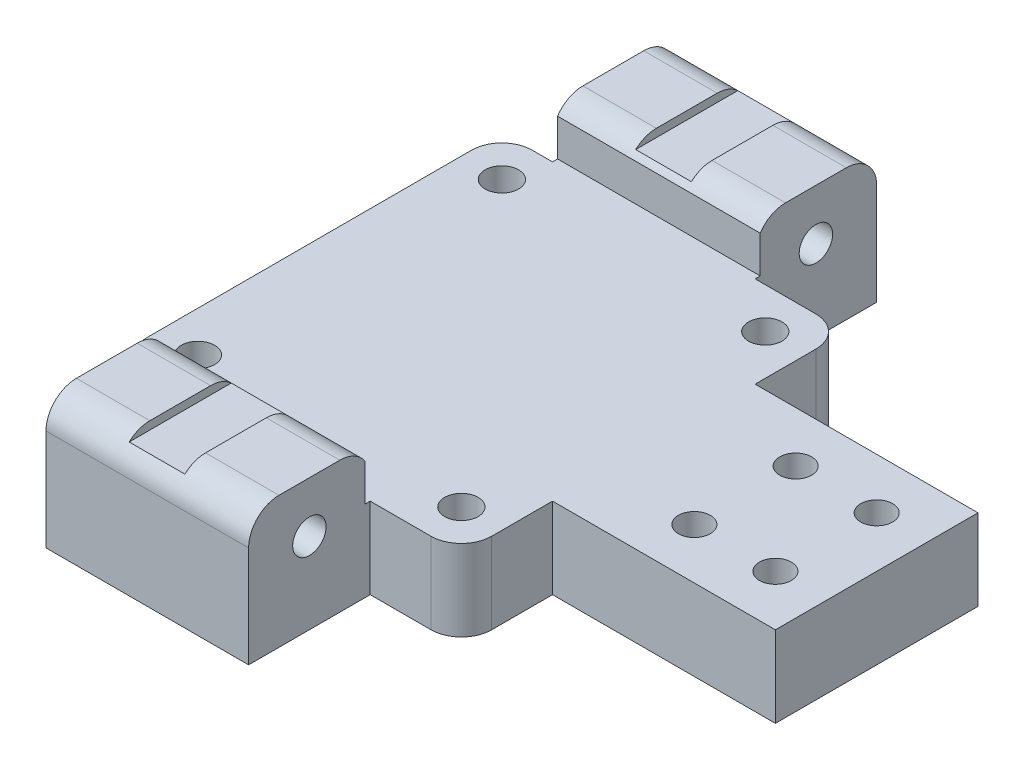
SolidWorks part; units mm, degrees
ref_plane "Front" through (0, 0, 0) normal (0, 0, 1) x (1, 0, 0)
ref_plane "Top" through (0, 0, 0) normal (0, 1, 0) x (1, 0, 0)
ref_plane "Right" through (0, 0, 0) normal (1, 0, 0) x (0, 0, -1)
sketch "Sketch1" plane through (0, 0, 0) normal (0, 1, 0) x (1, 0, 0)
  line L1 (0, 0) -> (300, 0)
  line L2 (0, 0) -> (0, -20)
  line L3 (0, -20) -> (300, -20)
  line L4 (300, 0) -> (300, -20)
  dimension "D1" = 20
  dimension "D2" = 300
extrude "Boss-Extrude1" add sketch "Sketch1" along normal blind 8
sketch "Sketch2" plane through (0, 0, 20) normal (0, 0, 1) x (1, 0, 0)
  line L0 (0, 8) -> (300, 8) construction
  line L1 (0, 0) -> (34, 0)
  line L2 (0, 0) -> (0, 8)
  line L3 (0, 8) -> (34, 8)
  line L4 (34, 0) -> (34, 8)
  line L5 (266, 8) -> (300, 8)
  line L6 (300, 0) -> (300, 8)
  line L7 (266, 0) -> (300, 0)
  line L8 (266, 0) -> (266, 8)
  dimension "D1" = 34
  dimension "D2" = 2
extrude "Boss-Extrude2" add sketch "Sketch2" along normal blind 9
sketch "Sketch3" plane through (0, 0, 0) normal (0, 0, -1) x (-1, 0, 0)
  line L0 (-300, 8) -> (0, 8) construction
  line L1 (0, 0) -> (-34, 0)
  line L2 (0, 0) -> (0, 8)
  line L3 (0, 8) -> (-34, 8)
  line L4 (-34, 0) -> (-34, 8)
  line L5 (-300, 0) -> (-300, 8)
  line L6 (-266, 8) -> (-300, 8)
  line L7 (-266, 0) -> (-266, 8)
  line L8 (-266, 0) -> (-300, 0)
  dimension "D1" = 34
  dimension "D2" = 2
extrude "Boss-Extrude3" add sketch "Sketch3" along normal blind 9
sketch "Sketch4" plane through (0, 8, 0) normal (0, 1, 0) x (1, 0, 0)
  line L0 (0, 9) -> (34, 9) construction
  line L1 (0, 9) -> (0, -29) construction
  circle A0 centre (4, 5) radius 1.65
  circle A1 centre (30, 5) radius 1.65
  circle A2 centre (30, -25) radius 1.65
  circle A3 centre (4, -25) radius 1.65
  circle A4 centre (296, -25) radius 1.65
  circle A5 centre (296, 5) radius 1.65
  circle A6 centre (270, -25) radius 1.65
  circle A7 centre (270, 5) radius 1.65
  dimension "D1" = 3.3
  dimension "D2" = 4
  dimension "D3" = 4
  dimension "D4" = 2
  dimension "D5" = 2
  dimension "D6" = 2
extrude "Cut-Extrude1" cut sketch "Sketch4" against normal through all
sketch "Sketch5" plane through (0, 0, 20) normal (0, 0, 1) x (1, 0, 0)
  line L0 (34, 8) -> (266, 8) construction
  line L1 (266, 0) -> (241, 0)
  line L2 (266, 0) -> (266, 8)
  line L3 (266, 8) -> (241, 8)
  line L4 (241, 0) -> (241, 8)
  dimension "D1" = 25
extrude "Boss-Extrude4" add sketch "Sketch5" along normal blind 17
sketch "Sketch6" plane through (0, 0, 0) normal (0, 0, -1) x (-1, 0, 0)
  line L0 (-266, 0) -> (-34, 0) construction
  line L1 (-266, 8) -> (-241, 8)
  line L2 (-266, 8) -> (-266, 0)
  line L3 (-266, 0) -> (-241, 0)
  line L4 (-241, 8) -> (-241, 0)
  dimension "D1" = 25
extrude "Boss-Extrude5" add sketch "Sketch6" along normal blind 17
sketch "Sketch7" plane through (0, 8, 0) normal (0, 1, 0) x (1, 0, 0)
  line L0 (266, -37) -> (241, -37) construction
  line L1 (259, -29) -> (249, -29)
  line L2 (259, -29) -> (259, 9)
  line L3 (259, 9) -> (249, 9)
  line L4 (249, -29) -> (249, 9)
  line L5 (241, -37) -> (241, -20) construction
  dimension "D1" = 10
  dimension "D2" = 38
  dimension "D3" = 8
  dimension "D4" = 8
extrude "Cut-Extrude2" cut sketch "Sketch7" against normal through all
sketch "Sketch8" plane through (0, 8, 0) normal (0, 1, 0) x (1, 0, 0)
  line L0 (259, -29) -> (259, 9) construction
  line L1 (259, -18) -> (266, -18)
  line L2 (259, -18) -> (259, -2)
  line L3 (259, -2) -> (266, -2)
  line L4 (266, -18) -> (266, -2)
  line L5 (266, -37) -> (241, -37) construction
  dimension "D1" = 7
  dimension "D2" = 16
  dimension "D3" = 19
extrude "Cut-Extrude3" cut sketch "Sketch8" against normal blind 4
sketch "Sketch9" plane through (259, 0, 0) normal (-1, 0, 0) x (0, 0, 1)
  line L0 (18, 4) -> (22, 8)
  line L1 (29, 8) -> (18, 8) construction
  line L2 (22, 8) -> (18, 8)
  line L3 (18, 8) -> (18, 4)
  line L4 (2, 4) -> (-2, 8)
  line L5 (2, 8) -> (-9, 8) construction
  line L6 (-2, 8) -> (2, 8)
  line L7 (2, 8) -> (2, 4)
  dimension "D1" = 4
  dimension "D2" = 4
extrude "Cut-Extrude4" cut sketch "Sketch9" against normal blind 7
sketch "Sketch10" plane through (259, 0, 0) normal (-1, 0, 0) x (0, 0, 1)
  line L0 (-9, 8) -> (-2, 0)
  line L1 (29, 0) -> (-9, 0) construction
  line L2 (-2, 0) -> (-9, 0)
  line L3 (-9, 0) -> (-9, 8)
  line L4 (29, 8) -> (22, 0)
  line L5 (22, 0) -> (29, 0)
  line L6 (29, 0) -> (29, 8)
  line L7 (-51.4523, 12.1971) -> (-51.8778, 12.5861)
  line M6 (-9, 8) -> (-9, 0)
  line M7 (-9, 0) -> (29, 0)
  line M8 (29, 0) -> (29, 8)
  dimension "D1" = 7
  dimension "D2" = 7
extrude "Boss-Extrude6" add sketch "Sketch10" along normal blind 10 contours L0 M6 M7 | L4 M8 M7
sketch "Sketch12" plane through (0, 0, 37) normal (0, 0, 1) x (1, 0, 0)
  line L0 (241, 0) -> (266, 0) construction
  line L1 (241, 8) -> (249, 8)
  line L2 (241, 8) -> (241, 0)
  line L3 (241, 0) -> (249, 0)
  line L4 (249, 8) -> (249, 0)
  dimension "D1" = 8
extrude "Boss-Extrude7" add sketch "Sketch12" along normal blind 17
sketch "Sketch13" plane through (0, 8, 0) normal (0, 1, 0) x (1, 0, 0)
  line L0 (249, -54) -> (241, -54) construction
  line L1 (249, -54) -> (249, -37) construction
  circle A0 centre (245, -50) radius 1.7
  circle A1 centre (245, -18) radius 1.7
  dimension "D1" = 3.4
  dimension "D2" = 4
  dimension "D3" = 4
  dimension "D4" = 2
extrude "Cut-Extrude6" cut sketch "Sketch13" against normal through all
sketch "Sketch14" plane through (0, 0, 29) normal (0, 0, 1) x (1, 0, 0)
  line L1 (295, 13) -> (275, 13)
  line L2 (295, 13) -> (295, 0)
  line L3 (295, 0) -> (275, 0)
  line L4 (275, 13) -> (275, 0)
  line L5 (266, 0) -> (300, 0) construction
  line L7 (266, 8) -> (266, 0) construction
  dimension "D1" = 20
  dimension "D2" = 9
  dimension "D3" = 13
extrude "Boss-Extrude8" add sketch "Sketch14" along normal blind 12
sketch "Sketch15" plane through (295, 0, 0) normal (1, 0, 0) x (0, 0, -1)
  line L0 (-41, 0) -> (-41, 13) construction
  line L1 (-41, 13) -> (-29, 13) construction
  circle A0 centre (-35, 8) radius 1.6
  dimension "D1" = 3.2
  dimension "D2" = 6
  dimension "D3" = 5
extrude "Cut-Extrude7" cut sketch "Sketch15" against normal blind 20
sketch "Sketch16" plane through (0, 0, -9) normal (0, 0, -1) x (-1, 0, 0)
  line L1 (-295, 13) -> (-275, 13)
  line L2 (-295, 13) -> (-295, 0)
  line L3 (-295, 0) -> (-275, 0)
  line L4 (-275, 13) -> (-275, 0)
  line L5 (-300, 0) -> (-266, 0) construction
  line L6 (-266, 0) -> (-266, 8) construction
  dimension "D1" = 20
  dimension "D2" = 9
  dimension "D3" = 13
extrude "Boss-Extrude9" add sketch "Sketch16" along normal blind 12
sketch "Sketch17" plane through (295, 0, 0) normal (1, 0, 0) x (0, 0, -1)
  line L1 (21, 13) -> (21, 0) construction
  line L2 (21, 13) -> (9, 13) construction
  circle A0 centre (15, 8) radius 1.6
  dimension "D1" = 3.2
  dimension "D2" = 5
  dimension "D3" = 6
extrude "Cut-Extrude8" cut sketch "Sketch17" against normal blind 20
sketch "Sketch18" plane through (0, 0, -9) normal (0, 0, -1) x (-1, 0, 0)
  line L1 (-25, 13) -> (-5, 13)
  line L2 (-25, 13) -> (-25, 0)
  line L3 (-25, 0) -> (-5, 0)
  line L4 (-5, 13) -> (-5, 0)
  line L5 (-34, 0) -> (0, 0) construction
  line L6 (-34, 8) -> (-34, 0) construction
  dimension "D1" = 20
  dimension "D2" = 9
  dimension "D3" = 13
extrude "Boss-Extrude10" add sketch "Sketch18" along normal blind 12
sketch "Sketch19" plane through (5, 0, 0) normal (-1, 0, 0) x (0, 0, 1)
  line L0 (-21, 0) -> (-21, 13) construction
  line L1 (-21, 13) -> (-9, 13) construction
  circle A0 centre (-15, 8) radius 1.65
  dimension "D1" = 3.3
  dimension "D2" = 6
  dimension "D3" = 5
extrude "Cut-Extrude9" cut sketch "Sketch19" against normal blind 20
sketch "Sketch20" plane through (0, 0, 29) normal (0, 0, 1) x (1, 0, 0)
  line L1 (5, 13) -> (25, 13)
  line L2 (5, 13) -> (5, 0)
  line L3 (5, 0) -> (25, 0)
  line L4 (25, 13) -> (25, 0)
  line L5 (0, 0) -> (34, 0) construction
  line L6 (34, 0) -> (34, 8) construction
  dimension "D1" = 20
  dimension "D2" = 9
  dimension "D3" = 13
extrude "Boss-Extrude11" add sketch "Sketch20" along normal blind 12
sketch "Sketch21" plane through (5, 0, 0) normal (-1, 0, 0) x (0, 0, 1)
  line L0 (41, 13) -> (41, 0) construction
  line L2 (41, 13) -> (29, 13) construction
  circle A0 centre (35, 8) radius 1.65
  dimension "D1" = 3.3
  dimension "D2" = 6
  dimension "D3" = 5
extrude "Cut-Extrude10" cut sketch "Sketch21" against normal blind 20
fillet "Fillet6" radius 3 8 edges at (15, 13, 41) (15, 13, 29) (15, 13, -9) (15, 13, -21) (285, 13, 41) (285, 13, 29) (285, 13, -9) (285, 13, -21)
sketch "Sketch22" plane through (300, 0, 0) normal (1, 0, 0) x (0, 0, -1)
  line L1 (-72.0035, 35.0177) -> (51.7473, 35.0177)
  line L2 (-72.0035, 35.0177) -> (-72.0035, -37.6215)
  line L3 (-72.0035, -37.6215) -> (51.7473, -37.6215)
  line L4 (51.7473, 35.0177) -> (51.7473, -37.6215)
extrude "Cut-Extrude11" cut sketch "Sketch22" against normal blind 244
sketch "Sketch23" plane through (0, 0, 0) normal (0, -1, 0) x (-1, 0, 0)
  line L0 (-34, -20) -> (-56, -20) construction
  line L1 (-56, -20) -> (-56, 0) construction
  line L2 (-56, 0) -> (-34, 0) construction
  circle A0 centre (-51, -5) radius 1.575
  circle A1 centre (-51, -15) radius 1.575
  circle A2 centre (-43, -5) radius 1.575
  circle A3 centre (-43, -15) radius 1.575
  dimension "D1" = 3.15
  dimension "D2" = 3.15
  dimension "D3" = 3.15
  dimension "D4" = 3.15
  dimension "D5" = 5
  dimension "D6" = 5
  dimension "D7" = 5
  dimension "D8" = 5
  dimension "D9" = 5
  dimension "D10" = 8
  dimension "D11" = 8
  dimension "D12" = 5
extrude "Cut-Extrude12" cut sketch "Sketch23" against normal through all
fillet "Fillet7" radius 3 4 edges at (0, 4, 29) (0, 4, -9) (34, 4, 29) (34, 4, -9)
sketch "Sketch24" plane through (0, 13, 0) normal (0, 1, 0) x (1, 0, 0)
  line L0 (5, 18) -> (5, 12) construction
  line L1 (12.25, 29.5448) -> (17.75, 29.5448)
  line L2 (12.25, 29.5448) -> (12.25, -48.6988)
  line L3 (12.25, -48.6988) -> (17.75, -48.6988)
  line L4 (17.75, 29.5448) -> (17.75, -48.6988)
  dimension "D1" = 5.5
  dimension "D2" = 7.25
extrude "Cut-Extrude13" cut sketch "Sketch24" against normal blind 0.8
sketch "Sketch25" plane through (0, 0, 29) normal (0, 0, -1) x (-1, 0, 0)
  line L1 (-25, 8) -> (-5, 8)
  line L2 (-25, 8) -> (-25, 13.7566)
  line L3 (-25, 13.7566) -> (-5, 13.7566)
  line L4 (-5, 8) -> (-5, 13.7566)
  dimension "D1" = 20
extrude "Cut-Extrude14" cut sketch "Sketch25" against normal blind 0.5
sketch "Sketch26" plane through (0, 0, -9) normal (0, 0, 1) x (1, 0, 0)
  line L1 (5, 8) -> (25, 8)
  line L2 (5, 8) -> (5, 29.4591)
  line L3 (5, 29.4591) -> (25, 29.4591)
  line L4 (25, 8) -> (25, 29.4591)
  dimension "D1" = 20
extrude "Cut-Extrude15" cut sketch "Sketch26" against normal blind 0.5
equation "\"滑动-垂直孔\" = 0.6"
equation "\"滑动-水平孔\"= 0.3"
equation "\"松动-垂直孔\" = 0.3"
equation "\"松动-水平孔\"= 0.1"
equation "\"正常-垂直孔\" = 0.15"
equation "\"正常-水平孔\"= 0"
equation "\"紧缩-垂直孔\"= 0"
equation "\"紧缩-水平孔\"= - 0.1"
equation "\"D2@Sketch23\"=\"正常-垂直孔\"+3"
equation "\"D4@Sketch23\"=\"正常-垂直孔\"+3"
equation "\"D1@Sketch23\"=\"正常-垂直孔\"+3"
equation "\"D3@Sketch23\"=\"正常-垂直孔\"+3"
equation "\"D1@Sketch4\"=\"松动-垂直孔\"+3"
equation "\"D1@Sketch19\"=\"滑动-水平孔\"+3"
equation "\"D1@Sketch21\"=\"滑动-水平孔\"+3"
